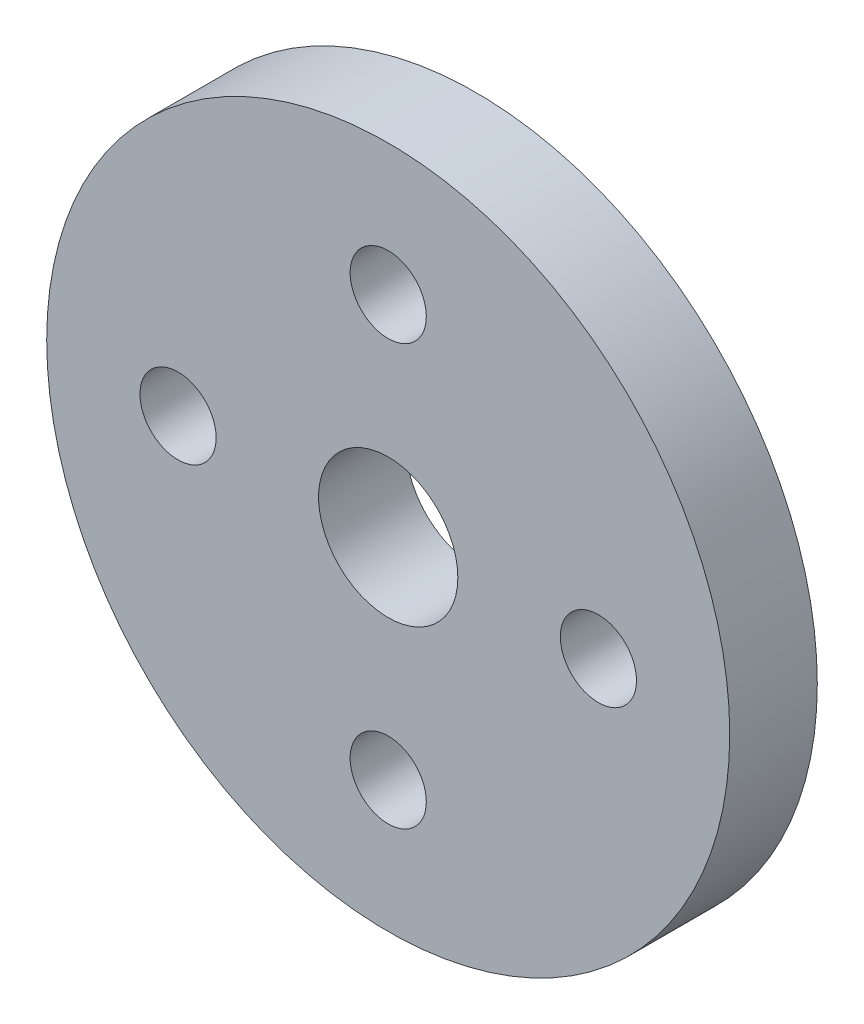
SolidWorks part; units mm, degrees
ref_plane "Front Plane" through (0, 0, 0) normal (0, 0, 1) x (1, 0, 0)
ref_plane "Top Plane" through (0, 0, 0) normal (0, 1, 0) x (1, 0, 0)
ref_plane "Right Plane" through (0, 0, 0) normal (1, 0, 0) x (0, 0, -1)
sketch "Sketch1" plane through (0, 0, 0) normal (0, 0, 1) x (1, 0, 0)
  circle A0 centre (0, 0) radius 19.5
  circle A2 centre (12, 0) radius 2.175
  circle A3 centre (0, 12) radius 2.175
  circle A4 centre (-12, 0) radius 2.175
  circle A5 centre (0, -12) radius 2.175
  circle A6 centre (0, 0) radius 3.975
  dimension "D1" = 4.35
  dimension "D2" = 4.35
  dimension "D3" = 4.35
  dimension "D4" = 4.35
  dimension "D5" = 7.95
  dimension "D6" = 39
extrude "Boss-Extrude1" add sketch "Sketch1" along normal blind 5
